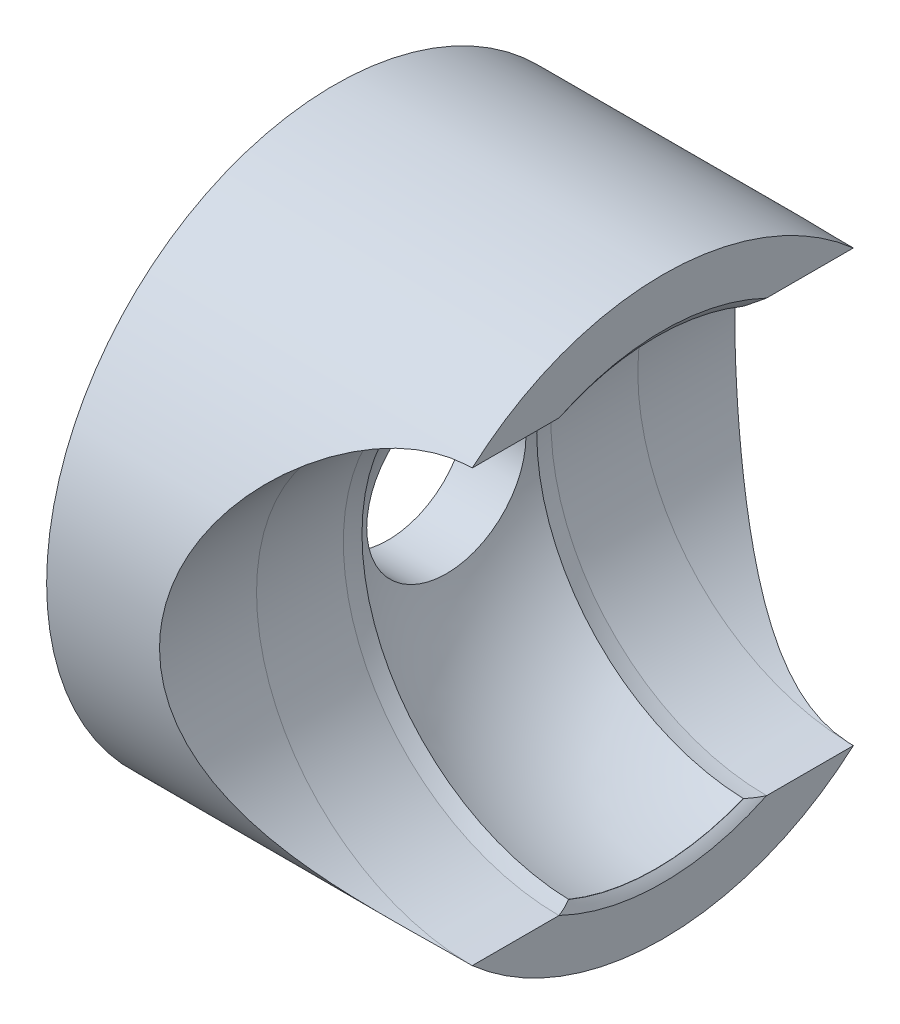
SolidWorks part; units mm, degrees
material "1023 Karbon Çeliği Levha (SS)"
ref_plane "Ön Düzlem" through (0, 0, 0) normal (0, 0, 1) x (1, 0, 0)
ref_plane "Üst Düzlem" through (0, 0, 0) normal (0, 1, 0) x (1, 0, 0)
ref_plane "Sağ Düzlem" through (0, 0, 0) normal (1, 0, 0) x (0, 0, -1)
sketch "Çizim1" plane through (0, 0, 0) normal (0, 1, 0) x (1, 0, 0)
  line L0 (0, 0) -> (9.8874, 0) construction
  line L1 (12.7815, 13.3831) -> (-2.503, 13.3831)
  line L2 (-2.5061, 13.204) -> (-2.5061, 9.6377)
  line L3 (-2.5061, 9.6377) -> (0, 9.6377)
  line L4 (0, 9.6377) -> (0, 3.705)
  line L5 (0, 3.705) -> (4.8086, 3.705)
  line L6 (12.7808, 11.1256) -> (12.7815, 13.3831)
  arc A0 (-2.5061, 13.204) -> (-2.503, 13.3831) centre (-3.7472, 13.3151) ccw
  arc A1 (5.1857, 3.559) -> (4.8086, 3.705) centre (4.7896, 3.0959) ccw
  arc A2 (12.4655, 10.7211) -> (5.1857, 3.559) centre (15.8522, -0.0021) ccw
  arc A3 (12.4655, 10.7211) -> (12.7808, 11.1256) centre (10.6602, 12.4531) ccw
revolve "Döndür1" add sketch "Çizim1" angle 360 about L0
ref_plane "Düzlem1" through (12.7739, 0, 0) normal (-1, 0, 0) x (0, 0, 1)
sketch "Çizim2" plane through (12.7739, 0, 0) normal (-1, 0, 0) x (0, 0, 1)
  line L0 (13.3852, 0) -> (-13.3852, 0)
  line L1 (8.8692, 10.025) -> (15.5184, 10.025)
  line L2 (15.5184, 10.025) -> (15.5184, 0)
  line L3 (15.5184, 0) -> (13.3852, 0)
  line L4 (-8.8692, 10.025) -> (-16.0778, 10.025)
  line L5 (-16.0778, 10.025) -> (-16.0778, 0)
  line L6 (-16.0778, 0) -> (-13.3852, 0)
  arc A0 (4.0653, 9.9227) -> (-4.0653, 9.9227) centre (0, 0) ccw
  spline S0 degree 3 poles (8.8692, 10.025) (7.5228, 10.0249) (6.1765, 10.0248) (4.8301, 10.0248) knots -0.011257 -0.011257 -0.011257 -0.011257 -0.007218 -0.007218 -0.007218 -0.007218
  spline S1 degree 3 poles (4.8301, 10.0248) (4.5672, 9.9983) (4.3105, 9.9664) (4.0653, 9.9227) knots 0 0 0 0 1 1 1 1
  spline S2 degree 3 poles (-4.0653, 9.9227) (-4.3097, 9.9663) (-4.5665, 9.9983) (-4.8301, 10.0248) knots 0 0 0 0 1 1 1 1
  spline S3 degree 3 poles (-4.8301, 10.0248) (-6.1765, 10.0248) (-7.5228, 10.0249) (-8.8692, 10.025) knots 0.002442 0.002442 0.002442 0.002442 0.006481 0.006481 0.006481 0.006481
revolve "Kes-Döndür3" cut sketch "Çizim2" angle 360 about L6
